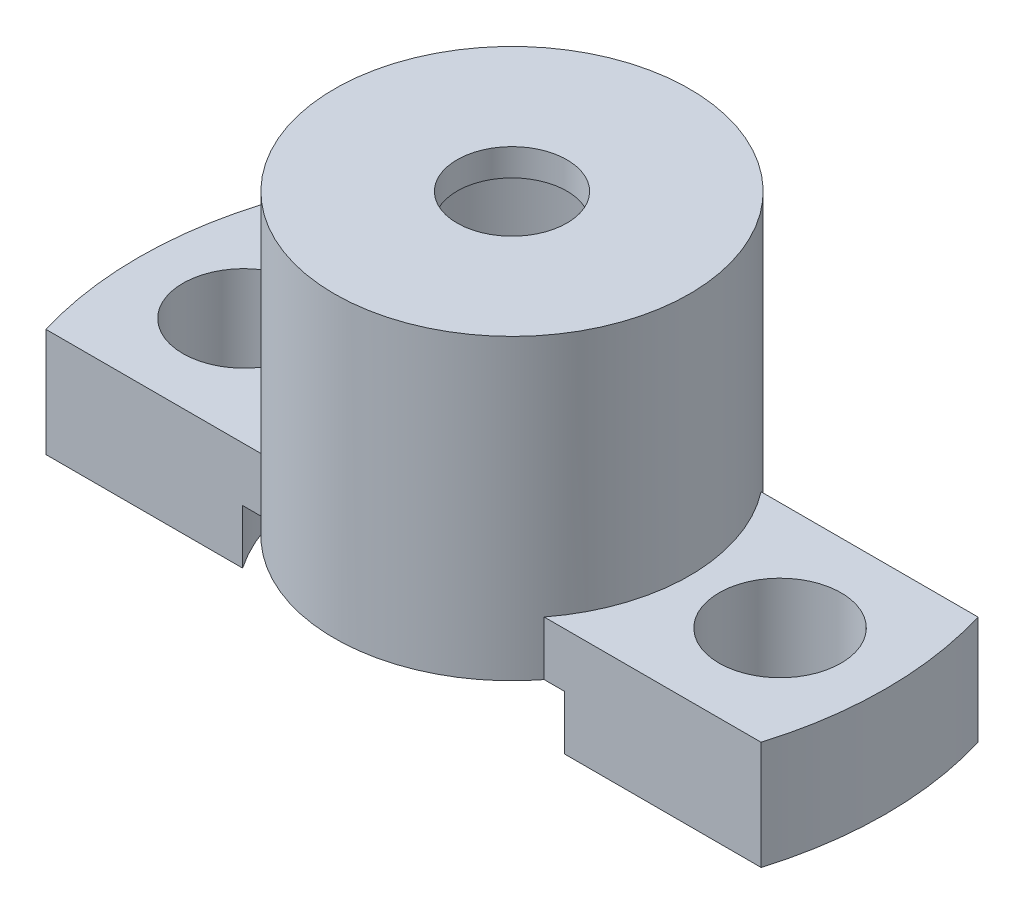
SolidWorks part; units mm, degrees
ref_plane "Front Plane" through (0, 0, 0) normal (0, 0, 1) x (1, 0, 0)
ref_plane "Top Plane" through (0, 0, 0) normal (0, 1, 0) x (1, 0, 0)
ref_plane "Right Plane" through (0, 0, 0) normal (1, 0, 0) x (0, 0, -1)
sketch "..." plane through (0, 0, 0) normal (0, 1, 0) x (1, 0, 0)
  circle A0 centre (0, 0) radius 5.55
  circle A1 centre (0, 0) radius 6.55
  dimension "D2" = 11.1
  dimension "D1" = 1
sketch "Sketch5" plane through (0, 0, 0) normal (0, 1, 0) x (-1, 0, 0)
  circle A0 centre (0, 0) radius 6.55
  circle A1 centre (0, 0) radius 2.025
  dimension "D1" = 4.05
  dimension "D2" = 13.1
extrude "Ext_TopMagnetRoom" add sketch "Sketch5" along normal blind 1
sketch "Sketch7" plane through (0, 0, 0) normal (0, -1, 0) x (1, 0, 0)
  circle A0 centre (0, 0) radius 5.05
  circle A1 centre (0, 0) radius 6.55
  circle A3 centre (0, 0) radius 6.55 construction
  dimension "D1" = 10.1
extrude "Ext_MagnetRoom" add sketch "Sketch7" along normal blind 4
sketch "Sketch6" plane through (0, -4, 0) normal (0, -1, 0) x (1, 0, 0)
  line L0 (13.1868, -4) -> (5.1868, -4)
  line L1 (-13.1868, -4) -> (-5.1868, -4)
  line L2 (-13.1868, 4) -> (-5.1868, 4)
  line L3 (5.1868, 4) -> (13.1868, 4)
  line L4 (13.7801, 0) -> (6.55, 0) construction
  line L5 (6.55, 0) -> (0, 0) construction
  line L6 (0, 0) -> (-6.55, 0) construction
  line L7 (-6.55, 0) -> (-13.7801, 0) construction
  line L10 (13.1868, -4) -> (13.1868, 4) construction
  arc A0 (13.1868, 4) -> (13.1868, -4) centre (0, 0) cw
  arc A1 (-13.1868, -4) -> (-13.1868, 4) centre (0, 0) cw
  arc A2 (5.1868, -4) -> (5.1868, 4) centre (0, 0) ccw
  arc A3 (-5.1868, -4) -> (-5.1868, 4) centre (0, 0) cw
  circle A4 centre (0, 0) radius 6.55 construction
extrude "Bottom-arms fixing with support" add sketch "Sketch6" against normal blind 2
sketch "Sketch9" plane through (0, -4, 0) normal (0, -1, 0) x (1, 0, 0)
  line L0 (13.1868, 4) -> (5.9368, 4)
  line L1 (13.1868, 4) -> (5.1868, 4) construction
  line L2 (-13.1868, -4) -> (-5.9368, -4)
  line L3 (-13.1868, -4) -> (-5.1868, -4) construction
  line L4 (-13.1868, 4) -> (-5.9368, 4)
  line L5 (13.1868, -4) -> (5.9368, -4)
  line L6 (-5.1868, 4) -> (-13.1868, 4) construction
  line L7 (5.1868, -4) -> (13.1868, -4) construction
  line L8 (-5.9368, 4) -> (-5.1868, 4) construction
  arc A1 (-13.1868, -4) -> (-13.1868, 4) centre (0, 0) cw
  arc A2 (13.1868, 4) -> (13.1868, -4) centre (0, 0) cw
  arc A3 (-5.9368, -4) -> (-5.9368, 4) centre (0, 0) cw
  arc A4 (5.9368, 4) -> (5.9368, -4) centre (0, 0) cw
  circle A5 centre (0, 0) radius 6.55 construction
  dimension "D1" = 0.75
extrude "Bottom- Fixing arms End" add sketch "Sketch9" along normal blind 2
sketch "Esquisse1" plane through (0, -2, 0) normal (0, 1, 0) x (1, 0, 0)
  circle A0 centre (-9.8868, 0) radius 2
  circle A1 centre (9.8868, 0) radius 2
  circle A4 centre (-9.8868, 0) radius 2.25 construction
  circle A5 centre (9.8868, 0) radius 2.25 construction
  dimension "D1" = 4
extrude "Ext_HoleMounted" cut sketch "Esquisse1" against normal through all
sketch "Sketch10" plane through (0, 1, 0) normal (0, 1, 0) x (1, 0, 0)
  circle A0 centre (0, 0) radius 5.05
  circle A1 centre (0, 0) radius 6.55
  circle A3 centre (0, 0) radius 5.05 construction
  circle A4 centre (0, 0) radius 6.55 construction
extrude "chamber" add sketch "Sketch10" along normal blind 5
sketch "Sketch11" plane through (0, 6, 0) normal (0, 1, 0) x (1, 0, 0)
  circle A0 centre (0, 0) radius 6.55
  circle A1 centre (0, 0) radius 2.025
  circle A3 centre (0, 0) radius 6.55 construction
  circle A6 centre (0, 0) radius 2.025 construction
extrude "Boss-Extrude4" add sketch "Sketch11" along normal blind 1
sketch "Esquisse2" [suppressed] plane through (0, 0, 0) normal (0, 0, 1) x (1, 0, 0)
  line L1 (26.7806, 17.3131) -> (-24.7319, 17.3131)
  line L2 (26.7806, 17.3131) -> (26.7806, -15.9722)
  line L3 (26.7806, -15.9722) -> (-24.7319, -15.9722)
  line L4 (-24.7319, 17.3131) -> (-24.7319, -15.9722)
extrude "Enlèv. mat.-Extru.1" [suppressed] cut sketch "Esquisse2" along normal through all
sketch "Esquisse3" plane through (0, -2, 0) normal (0, 1, 0) x (1, 0, 0)
  circle A0 centre (9.8868, 0) radius 3
  circle A1 centre (-9.8868, 0) radius 3
  circle A2 centre (9.8868, 0) radius 2 construction
  arc A3 (-11.4876, -1.1989) -> (-11.4876, 1.1989) centre (-9.8868, 0) ccw construction
  dimension "D1" = 1
extrude "Enlèv. mat.-Extru.2" cut sketch "Esquisse3" along normal through all
sketch "Sketch12" plane through (0, -6, 0) normal (0, -1, 0) x (1, 0, 0)
  circle A0 centre (-9.8868, 0) radius 2.5
  circle A1 centre (9.8868, 0) radius 2.5
  dimension "D1" = 5
  dimension "D2" = 5
extrude "Cut-Extrude1" [suppressed] cut sketch "Sketch12" against normal blind 10
sketch "Sketch13" plane through (0, -4, 0) normal (0, -1, 0) x (1, 0, 0)
  circle A0 centre (0, 0) radius 5.2
  dimension "D1" = 10.4
extrude "Cut-Extrude2" cut sketch "Sketch13" against normal up to surface (4 mm away) up to face at (0, 0, 2.025)
sketch "Sketch14" plane through (0, -2, 0) normal (0, 1, 0) x (1, 0, 0)
  circle A0 centre (-9.8868, 0) radius 2.25
  circle A1 centre (9.8868, 0) radius 2.25
  dimension "D1" = 4.5
  dimension "D2" = 4.5
extrude "Cut-Extrude3" cut sketch "Sketch14" against normal blind 10
sketch "Sketch15" plane through (0, -4, 0) normal (0, -1, 0) x (1, 0, 0)
  circle A0 centre (0, 0) radius 6.1
  dimension "D1" = 12.2
extrude "Cut-Extrude4" cut sketch "Sketch15" against normal up to surface (4 mm away) up to face at (0, 0, 2.025)
equation "\"magnet_DI\"= 3mm'inner diameter of the o-ring magnet"
equation "\"magnet_DE\"= 8mm'external diameter of the o-ring magnet"
equation "\"magnet_H\"= 3mm'tall of the magnet"
equation "\"magnet_levitation_DI\"= 0mm'inner diameter of the o-ring magnet"
equation "\"magnet_levitation_DE\"= 1mm'external diameter of the o-ring magnet"
equation "\"magnet_levitation_H\"= 0.5mm'tall of the magnet"
equation "\"gap_magnet_H\"= 1mm'gap between the 2 magnets"
equation "\"plug_DI\"= 1.5mm'size of the inner extrude of the plug (finger contact)"
equation "\"coil_H\"= 8mm 'height coil"
equation "\"coil_W\"= 0.2mm 'width coil"
equation "\"mandrine_freegap\"= 0.2mm 'gap between the magnet and the mandrine. "
equation "\"mandrine_bottom_H\"= 0.5mm 'border of the bottom of the mandrine"
equation "\"mandrine_coilmagnet_wall\"= 0.15mm"
equation "\"mandrine_magnet_lev\"= 3mm' gap needed for the levitation of the rod"
equation "\"mandrine_border_H\"= 2mm 'border of the top of the mandrine"
equation "\"mandrine_epoxy_W\"= 0.5mm 'width epoxy"
equation "\"mandrine_DI\"= \"mandrine_freegap\"*2+\"magnet_DE\""
equation "\"mandrine_DE\"= (\"mandrine_epoxy_W\"+\"coil_W\"+\"mandrine_coilmagnet_wall\")*2+\"mandrine_DI\""
equation "\"mandrine_H\"= \"magnet_levitation_H\"+\"mandrine_magnet_lev\"+\"magnet_H\"+\"gap_magnet_H\"/2+\"coil_H\"/2+\"mandrine_border_H\""
equation "\"mandrine_hat_W\"= 1mm"
equation "\"tower_freegap\"= 1mm 'gap between the actuator and the tower"
equation "\"tower_DI\"= \"mandrine_DE\"+\"tower_freegap\""
equation "\"tower_W\"= 1mm'width of the tower"
equation "\"tower_link_H\"= 2mm"
equation "\"tower_link_W\"= 4mm"
equation "\"tower_channel_W\"= 1mm"
equation "\"tower_renforcement_H\"= 2mm"
equation "\"apex_tower_Dbase\"= 2.5mm 'diameter of the holes in order to curve"
equation "\"apex_tower_Rbase1\"= 0.75mm 'diameter of the holes in order to curve"
equation "\"apex_tower_Rbase2\"= 1mm 'diameter of the holes in order to curve"
equation "\"apex_tower_Rbase3\"= 1.25mm 'diameter of the holes in order to curve"
equation "\"apex_tower_holeOpening1\"= \"apex_tower_Rbase1\"*7/8"
equation "\"apex_tower_holeOpening2\"= \"apex_tower_Rbase2\"*7/8"
equation "\"apex_tower_holeOpening3\"= \"apex_tower_Rbase3\"*7/8"
equation "\"apex_tower_Hbase\"= 1mm 'gap between the bottom of the tower and the holes"
equation "\"apex_tower_hole\"= 4.5mm 'witdh of the hole"
equation "\"apex_tower_H\"= 0mm '\"mandrine_H\"-\"tower_link_H\""
equation "\"apex_tower_H2\"= \"apex_tower_H\"+7mm"
equation "\"actuator1.x\"= 42.59mm"
equation "\"actuator2.x\"= 80.026mm"
equation "\"actuator3.x\"= 0mm"
equation "\"actuator4.x\"= 14.55mm"
equation "\"actuator5.x\"= 14.557mm"
equation "\"actuator6.x\"= 12.497mm"
equation "\"actuator7.x\"= 27.494mm"
equation "\"actuator8.x\"= 39.75mm"
equation "\"actuator9.x\"= 41.5767mm"
equation "\"actuator10.x\"= 41.148mm"
equation "\"actuator11.x\"= 70.869mm"
equation "\"actuator12.x\"= 77.15mm"
equation "\"actuator13.x\"= 70.87mm"
equation "\"actuator14.x\"= 80.15mm"
equation "\"actuator15.x\"= 92.21mm"
equation "\"actuator16.x\"= 97.61mm"
equation "\"actuator17.x\"= 87.41mm"
equation "\"actuator18.x\"= 109.08mm"
equation "\"actuator19.x\"= 125.04mm"
equation "\"actuator20.x\"= 119.466mm"
equation "\"actuator21.x\"= 115.558mm"
equation "\"actuator22.x\"= 142.74mm"
equation "\"actuator23.x\"= 145.93mm"
equation "\"actuator24.x\"= 131.11mm"
equation "\"actuator1.y\"= 101.167mm"
equation "\"actuator2.y\"= 120.647mm"
equation "\"actuator3.y\"= 45.677mm"
equation "\"actuator4.y\"= 66.047mm"
equation "\"actuator5.y\"= 45.327mm"
equation "\"actuator6.y\"= 28.807mm"
equation "\"actuator7.y\"= 13.807mm"
equation "\"actuator8.y\"= 30.087mm"
equation "\"actuator9.y\"= 49.157mm"
equation "\"actuator10.y\"= 71.787mm"
equation "\"actuator11.y\"= 78.407mm"
equation "\"actuator12.y\"= 52.377mm"
equation "\"actuator13.y\"= 25.793mm"
equation "\"actuator14.y\"= 0.711mm"
equation "\"actuator15.y\"= 34.092mm"
equation "\"actuator16.y\"= 57.427mm"
equation "\"actuator17.y\"= 86.987mm"
equation "\"actuator18.y\"= 92.077mm"
equation "\"actuator19.y\"= 63.187mm"
equation "\"actuator20.y\"= 34.434mm"
equation "\"actuator21.y\"= 0mm"
equation "\"actuator22.y\"= 38.901mm"
equation "\"actuator23.y\"= 70.278mm"
equation "\"actuator24.y\"= 100.8741mm"
equation "\"actuator1.z\"= 45.834mm"
equation "\"actuator2.z\"= 37.834mm"
equation "\"actuator3.z\"= 13mm"
equation "\"actuator4.z\"= 33.9226mm"
equation "\"actuator5.z\"= 51.234mm"
equation "\"actuator6.z\"= 29.9773mm"
equation "\"actuator7.z\"= 49.434mm"
equation "\"actuator8.z\"= 31.7209mm"
equation "\"actuator9.z\"= 60.084mm"
equation "\"actuator10.z\"= 45.3632mm"
equation "\"actuator11.z\"= 42.0948mm"
equation "\"actuator12.z\"= 33.6927mm"
equation "\"actuator13.z\"= 48.7255mm"
equation "\"actuator14.z\"= 45.0141mm"
equation "\"actuator15.z\"= 63.034mm"
equation "\"actuator16.z\"= 50.5713mm"
equation "\"actuator17.z\"= 61.634mm"
equation "\"actuator18.z\"= 46.3531mm"
equation "\"actuator19.z\"= 57.834mm"
equation "\"actuator20.z\"= 58.534mm"
equation "\"actuator21.z\"= 44.984mm"
equation "\"actuator22.z\"= 45.5969mm"
equation "\"actuator23.z\"= 42.2671mm"
equation "\"actuator24.z\"= 33.4578mm"
equation "\"shape_freegap\"= \"tower_freegap\""
equation "\"shape_strip_witdh\"= 5mm"
equation "\"shape_holes_sweat_D\"= 2mm"
equation "\"shape_holes_actuator_D\"= \"magnet_DE\"+\"shape_freegap\"+1mm"
equation "\"shape_holes_actuator_extD\"= \"shape_holes_actuator_D\"+2*\"shape_strip_witdh\""
equation "\"shape_holes_wet_D\"= 2mm"
equation "\"amortisseur_Dext\"= 18mm"
equation "\"amortisseur_Din\"= 7mm"
equation "\"amortisseur_H\"= 20mm"
equation "\"amortisseur_prise_D\"= 10mm"
equation "\"amortisseur_bourlet_H\"= 0.5mm"
equation "\"fixation_prise_base_D\"= (\"amortisseur_prise_D\"+3)"
equation "\"fixation_prise_base_H\"= 1mm"
equation "\"fixation_prise_tete_D\"= (\"amortisseur_Dext\"+3)"
equation "\"fixation_prise_tete_H\"= 2.5mm"
equation "\"fixation_D\"= \"fixation_prise_tete_D\" + 2mm"
equation "\"fixation_H\"= \"fixation_prise_base_H\" + \"fixation_prise_tete_H\" + 3mm"
equation "\"fixation_zone_accroche_D\"= 3*\"fixation_D\""
equation "\"oring_R\"= 0.75mm"
equation "\"oring_R1\"= 0.25mm"
equation "\"oring_R2\"= 0.3mm"
equation "\"oring_R3\"= 0.75mm"
equation "\"guide_H1\"=4mm"
equation "\"guide_H2\"=1mm"
equation "\"guide_W1\"=1mm"
equation "\"guide_openAngle\"=360deg"
equation "\"guide_ecrou_DI\"=5mm"
equation "\"guide_ecrou_DE\"=8mm"
equation "\"guide_vis_DI\"=4mm"
equation "\"guide_rondelle_DE\"=9mm"
equation "\"D1@...\" = \"guide_W1\""
equation "\"D2@...\" = \"tower_DI\""
equation "\"D2@Sketch5\"=\"tower_DI\"+\"tower_W\"*2"
equation "\"D1@Sketch5\"=\"magnet_DI\"+1.05"
equation "\"D1@Ext_TopMagnetRoom\" = \"guide_W1\""
equation "\"D1@Ext_MagnetRoom\" = \"guide_H1\""
equation "\"D1@Sketch7\"=\"mandrine_DE\""
